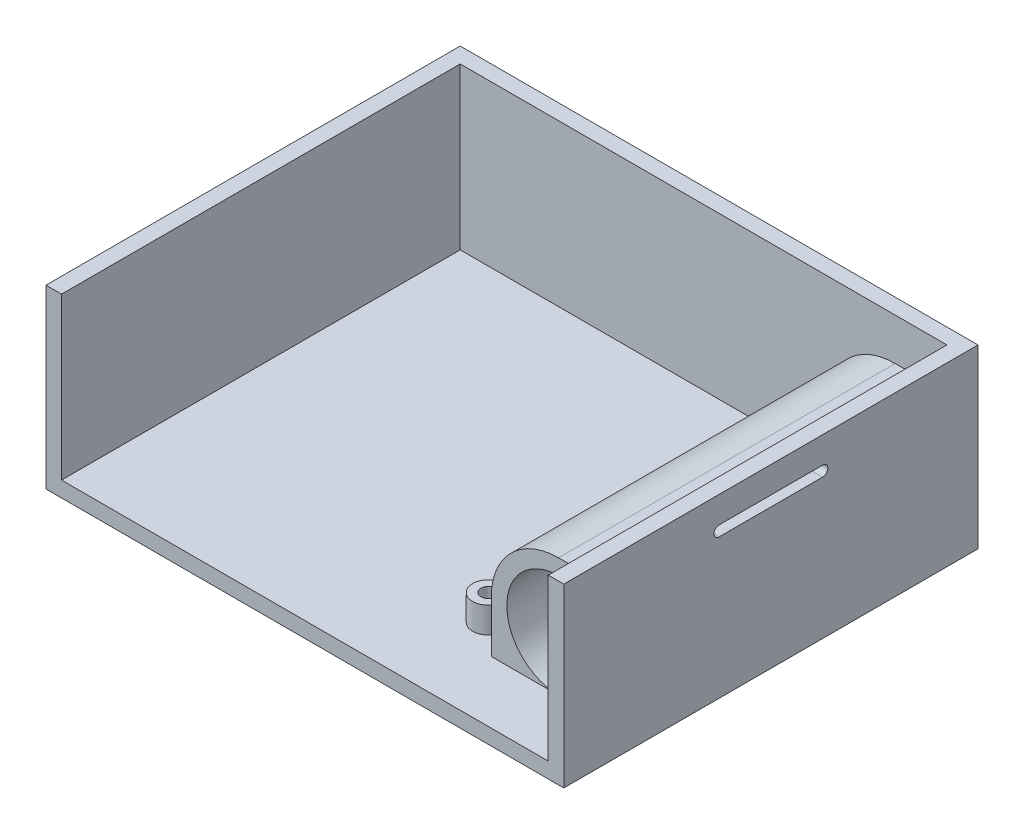
SolidWorks part; units mm, degrees
ref_plane "Front Plane" through (0, 0, 0) normal (0, 0, 1) x (1, 0, 0)
ref_plane "Top Plane" through (0, 0, 0) normal (0, 1, 0) x (1, 0, 0)
ref_plane "Right Plane" through (0, 0, 0) normal (1, 0, 0) x (0, 0, -1)
sketch "Sketch1" plane through (0, 0, 0) normal (0, 1, 0) x (1, 0, 0)
  line L1 (-50, -40) -> (50, -40)
  line L2 (-50, -40) -> (-50, 40)
  line L3 (-50, 40) -> (50, 40)
  line L4 (50, -40) -> (50, 40)
  line L5 (-50, -40) -> (50, 40) construction
  line L6 (-50, 40) -> (50, -40) construction
  point P0 (0, 0)
  dimension "D1" = 100
  dimension "D2" = 80
extrude "Boss-Extrude1" add sketch "Sketch1" along normal blind 3
sketch "Sketch2" plane through (0, 3, 0) normal (0, 1, 0) x (1, 0, 0)
  line L1 (-50, 40) -> (50, 40)
  line L2 (-50, 40) -> (-50, -40)
  line L3 (-50, -40) -> (-47, -40)
  line L4 (50, 40) -> (50, -40)
  line L5 (-50, 40) -> (-50, -40) construction
  line L7 (47, 37) -> (47, -40)
  line L8 (-47, 37) -> (47, 37)
  line L9 (-47, 37) -> (-47, -40)
  line L12 (47, -40) -> (50, -40)
  line L20 (50, 40) -> (-50, 40) construction
  point P0 (0, 0)
  dimension "D1" = 3
  dimension "D2" = 3
  dimension "D3" = 3
extrude "Boss-Extrude2" add sketch "Sketch2" along normal blind 31.1
sketch "Sketch3" plane through (0, 0, -37) normal (0, 0, 1) x (1, 0, 0)
  line L0 (-47, 3) -> (47, 3) construction
  line L1 (47, 34.1) -> (47, 3) construction
  line L2 (37, 26) -> (47, 26)
  line L3 (24, 13) -> (24, 3)
  line L4 (-47, 3) -> (47, 3) construction
  circle A0 centre (37, 13) radius 10
  arc A1 (37, 26) -> (24, 13) centre (37, 13) ccw
  circle A2 centre (37, 13) radius 13 construction
  line M1 (-47, 3) -> (47, 3)
  line M2 (47, 3) -> (47, 34.1)
  dimension "D1" = 20
  dimension "D2" = 3
extrude "Boss-Extrude3" add sketch "Sketch3" along normal blind 65 contours L2 A1 L3 A0 M1 M2 | A0 M1 M2
sketch "Sketch4" plane through (0, 3, 0) normal (0, 1, 0) x (1, 0, 0)
  line L0 (-47, 37) -> (24, 37) construction
  line L1 (24, -28) -> (24, 37) construction
  circle A0 centre (18, 22) radius 3
  circle A1 centre (18, 22) radius 1.425
  dimension "D1" = 6
  dimension "D4" = 2.85
  dimension "D2" = 15
  dimension "D3" = 6
extrude "Boss-Extrude4" add sketch "Sketch4" along normal blind 5
pattern_linear "LPattern1" count 2 spacing 44.6 along (0, 0, 1) of "Boss-Extrude4"
sketch "Sketch10" plane through (47, 0, 0) normal (-1, 0, 0) x (0, 0, 1)
  line L0 (-10, 28) -> (10, 28) construction
  line L1 (-10, 29) -> (10, 29)
  line L2 (-10, 27) -> (10, 27)
  line L3 (28, 26) -> (-37, 26) construction
  arc A0 (-10, 29) -> (-10, 27) centre (-10, 28) ccw
  arc A1 (10, 27) -> (10, 29) centre (10, 28) ccw
  point P2 (0, 28)
  point P7 (0, 0)
  dimension "D1" = 2
  dimension "D2" = 2
  dimension "D3" = 20
extrude "Cut-Extrude1" cut sketch "Sketch10" against normal through all
